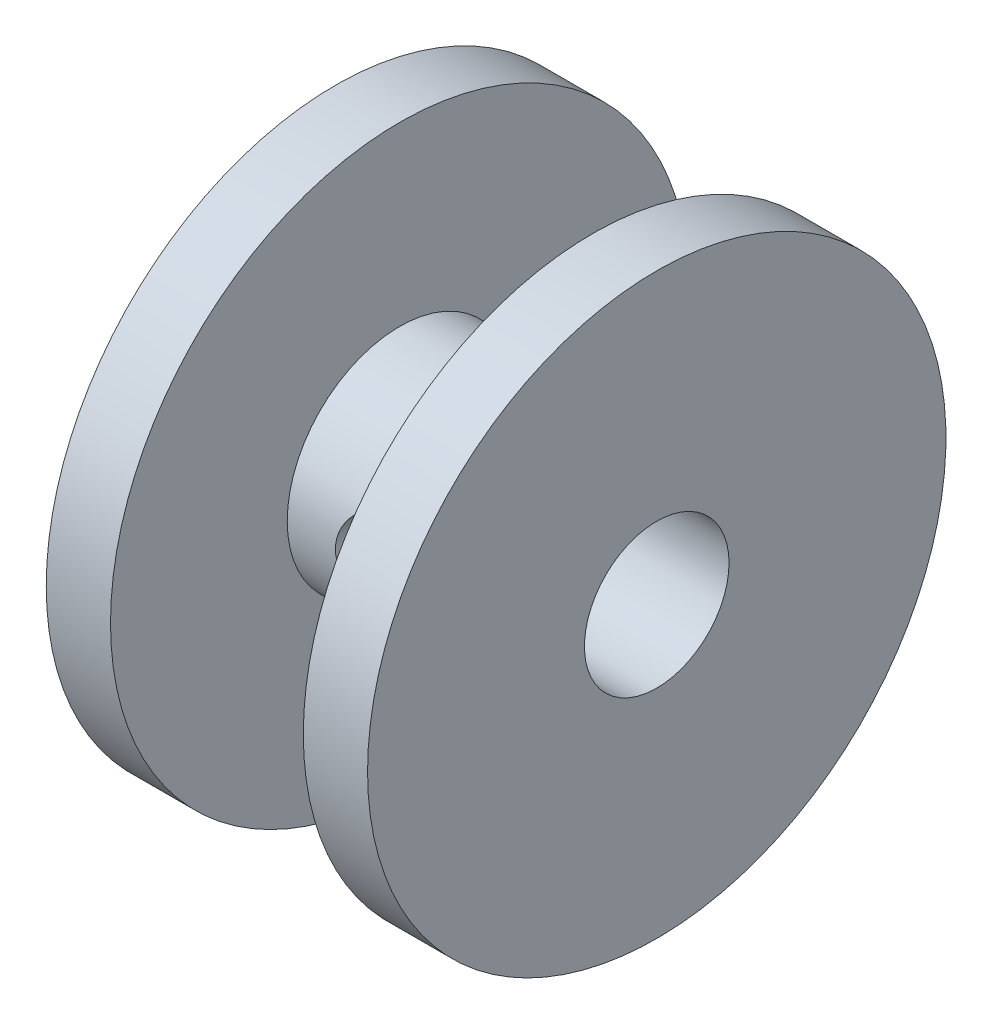
SolidWorks part; units mm, degrees
ref_plane "Front Plane" through (0, 0, 0) normal (0, 0, 1) x (1, 0, 0)
ref_plane "Top Plane" through (0, 0, 0) normal (0, 1, 0) x (1, 0, 0)
ref_plane "Right Plane" through (0, 0, 0) normal (1, 0, 0) x (0, 0, -1)
sketch "Sketch1" plane through (0, 0, 0) normal (0, 0, 1) x (1, 0, 0)
  line L20 (-85.1361, -10.256) -> (-85.1361, -19.256)
  line L21 (-85.1361, -19.256) -> (-75.1361, -19.256)
  line L22 (-75.1361, -19.256) -> (-75.1361, -10.256)
  line L23 (-75.1361, -10.256) -> (-77.1361, -10.256)
  line L24 (-77.1361, -10.256) -> (-77.1361, -15.756)
  line L25 (-77.1361, -15.756) -> (-83.1361, -15.756)
  line L26 (-83.1361, -15.756) -> (-83.1361, -10.256)
  line L27 (-83.1361, -10.256) -> (-85.1361, -10.256)
  dimension "D1" = 6
  dimension "D2" = 2
  dimension "D3" = 3.5
  dimension "D4" = 9
revolve "Revolve2" add sketch "Sketch1" angle 360 about L21
sketch "Sketch2" plane through (-75.1361, 0, 0) normal (1, 0, 0) x (0, 0, -1)
  circle A0 centre (0, -19.256) radius 2.25
  circle A2 centre (0, -19.256) radius 9 construction
  point P2 (0, 0)
  point P3 (0, 0)
  point P4 (0, 0)
extrude "Cut-Extrude1" cut sketch "Sketch2" against normal through all
ref_plane "Plane1" through (0, 0, 0) normal (0, 0, 1) x (1, 0, 0)
sketch "Sketch5" plane through (0, 0, 0) normal (0, 0, 1) x (1, 0, 0)
  line L0 (-75.1361, -28.256) -> (-75.1361, -10.256) construction
  line L2 (-83.1361, -22.756) -> (-77.1361, -22.756) construction
  circle A0 centre (-80.1361, -19.256) radius 1.5
  point P6 (-75.9207, -24.6385)
  dimension "D2" = 3
  dimension "D1" = 5
  dimension "D3" = 3.5
extrude "Cut-Extrude2" cut sketch "Sketch5" against normal through all both and the other way through all
